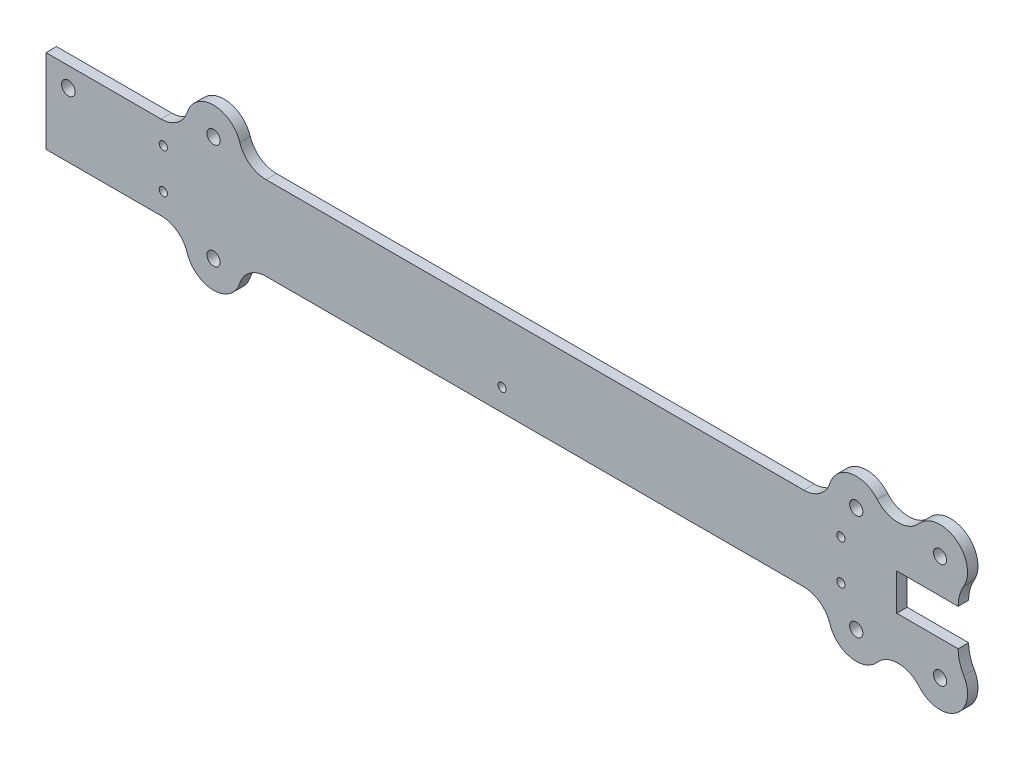
SolidWorks part; units mm, degrees
ref_plane "Front Plane" through (0, 0, 0) normal (0, 0, 1) x (1, 0, 0)
ref_plane "Top Plane" through (0, 0, 0) normal (0, 1, 0) x (1, 0, 0)
ref_plane "Right Plane" through (0, 0, 0) normal (1, 0, 0) x (0, 0, -1)
sketch "Sketch1" plane through (0, 0, 0) normal (0, 0, 1) x (1, 0, 0)
  line L0 (553.1, 14.28) -> (553.1, 5.7479) construction
  line L1 (0, 50.8) -> (69.7828, 50.8)
  line L2 (0, 50.8) -> (0, 0)
  line L3 (0, 0) -> (69.7828, 0)
  line L4 (553.1, 45.0521) -> (553.1, 36.52) construction
  line L5 (515.86, 36.52) -> (553.1, 36.52)
  line L6 (515.86, 36.52) -> (515.86, 14.28)
  line L7 (515.86, 14.28) -> (553.1, 14.28)
  line L8 (101.6, 57.34) -> (101.6, 77.1011) construction
  line L9 (133.4172, 50.8) -> (459.4828, 50.8)
  line L10 (0, 25.4) -> (553.1, 25.4) construction
  line L12 (0, 25.4) -> (457.2, 25.4) construction
  line L13 (133.4172, 0) -> (459.4828, 0)
  line L14 (515.86, 46.34) -> (515.86, 4.46) construction
  line L15 (528.56, 36.52) -> (553.1, 36.52) construction
  line L16 (0, 50.8) -> (553.1, 50.8) construction
  circle A0 centre (13.54, 38.94) radius 4 construction
  circle A1 centre (13.54, 38.94) radius 4.127
  circle A2 centre (101.6, -6.54) radius 4
  arc A3 (133.4172, 0) -> (117.5086, -11.62) centre (133.4172, -16.7) ccw
  arc A4 (69.7828, 0) -> (85.6914, -11.62) centre (69.7828, -16.7) cw
  arc A5 (117.5086, -11.62) -> (85.6914, -11.62) centre (101.6, -6.54) cw
  arc A6 (556.4711, 48.8335) -> (529.4, 68.1844) centre (542.1, 57.34) ccw
  circle A7 centre (71.12, 37.4575) radius 2.4892 construction
  circle A8 centre (13.54, 38.94) radius 11 construction
  circle A12 centre (481.98, 13.3425) radius 2.4892
  circle A13 centre (481.98, 37.4575) radius 2.4892
  circle A14 centre (276.55, 13.3425) radius 2.4892
  circle A15 centre (71.12, 13.3425) radius 2.4892
  circle A16 centre (71.12, 37.4575) radius 2.4892
  circle A17 centre (101.6, 57.34) radius 4
  arc A18 (117.5086, 62.42) -> (85.6914, 62.42) centre (101.6, 57.34) ccw
  arc A19 (69.7828, 50.8) -> (85.6914, 62.42) centre (69.7828, 67.5) ccw
  arc A21 (133.4172, 50.8) -> (117.5086, 62.42) centre (133.4172, 67.5) cw
  circle A22 centre (101.6, 57.34) radius 16.7 construction
  arc A23 (504, 68.1844) -> (475.3914, 62.42) centre (491.3, 57.34) ccw
  circle A24 centre (491.3, 57.34) radius 4
  circle A25 centre (542.1, 57.34) radius 4
  arc A27 (556.4711, 1.9665) -> (529.4, -17.3844) centre (542.1, -6.54) cw
  circle A28 centre (542.1, -6.54) radius 4
  circle A29 centre (491.3, -6.54) radius 4
  arc A30 (504, -17.3844) -> (475.3914, -11.62) centre (491.3, -6.54) cw
  arc A31 (504, 68.1844) -> (529.4, 68.1844) centre (516.7, 79.0287) ccw
  arc A32 (504, -17.3844) -> (529.4, -17.3844) centre (516.7, -28.2287) cw
  arc A33 (459.4828, 50.8) -> (475.3914, 62.42) centre (459.4828, 67.5) ccw
  arc A34 (459.4828, 0) -> (475.3914, -11.62) centre (459.4828, -16.7) cw
  arc A35 (553.1, 36.52) -> (556.4711, 48.8335) centre (577.2739, 36.52) cw
  arc A36 (553.1, 14.28) -> (556.4711, 1.9665) centre (577.2739, 14.28) ccw
  point P11 (0, 0)
  point P14 (542.1, -6.54)
  point P18 (0, 0)
  point P20 (0, 0)
  point P22 (515.86, 15.2135)
  point P57 (553.1, 36.52)
  point P59 (459.4849, 50.8)
  point P81 (0, 0)
  point P87 (101.6, 57.34)
  point P89 (57.9621, 37.4575)
  point P93 (0, 0)
  point P94 (0, 0)
  point P97 (0, 0)
  point P98 (0, 0)
  point P102 (0, 0)
  point P104 (481.98, 37.4575)
  point P106 (481.98, 13.3425)
  point P108 (71.12, 37.4575)
  dimension "D1" = 8
  dimension "D3" = 8
  dimension "D2" = 0.127
  dimension "D4" = 12.7
extrude "Boss-Extrude1" add sketch "Sketch1" along normal blind 6.35
